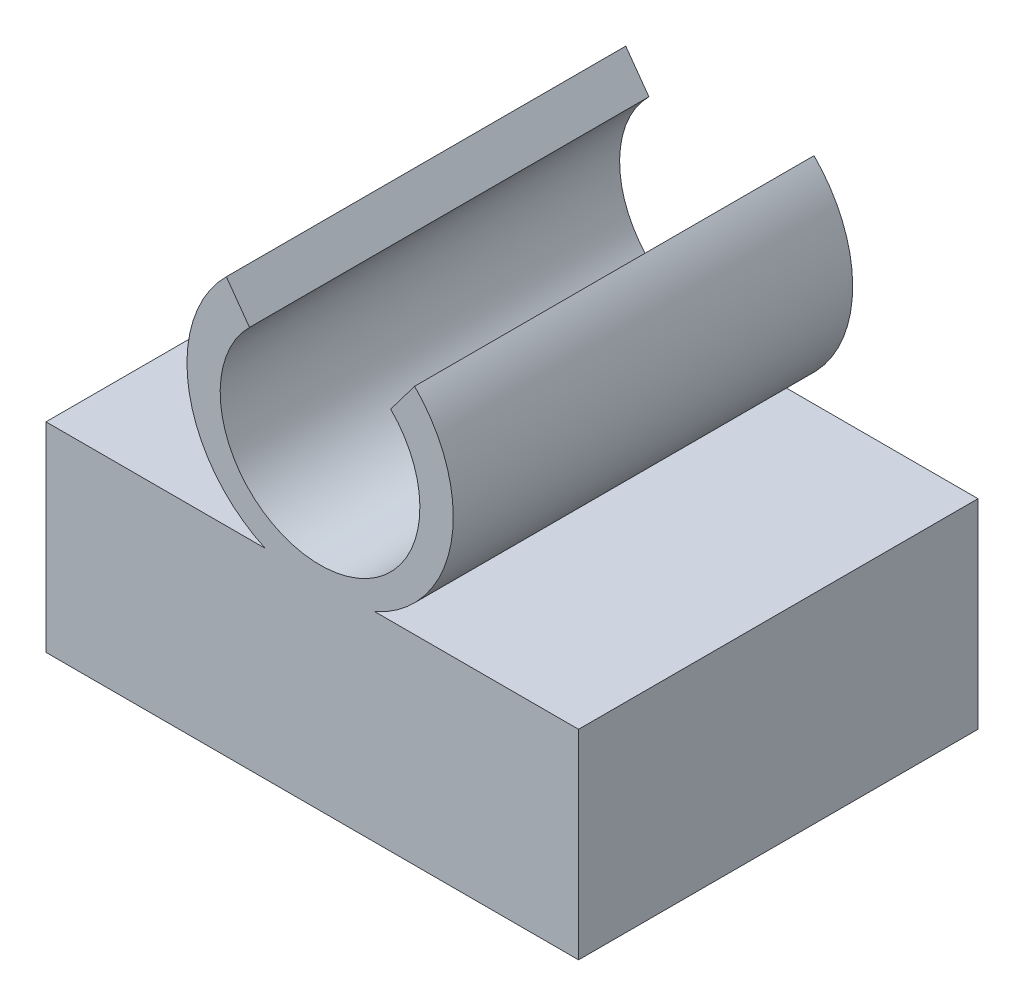
SolidWorks part; units mm, degrees
ref_plane "Front Plane" through (0, 0, 0) normal (0, 0, 1) x (1, 0, 0)
ref_plane "Top Plane" through (0, 0, 0) normal (0, 1, 0) x (1, 0, 0)
ref_plane "Right Plane" through (0, 0, 0) normal (1, 0, 0) x (0, 0, -1)
sketch "Sketch1" plane through (0, 0, 0) normal (0, 1, 0) x (1, 0, 0)
  line L1 (-33.5398, 47.0575) -> (46.4602, 47.0575)
  line L2 (-33.5398, 47.0575) -> (-33.5398, -12.9425)
  line L3 (-33.5398, -12.9425) -> (46.4602, -12.9425)
  line L4 (46.4602, 47.0575) -> (46.4602, -12.9425)
  dimension "D1" = 60
  dimension "D2" = 80
extrude "Boss-Extrude2" add sketch "Sketch1" along normal blind 30
sketch "Sketch2" plane through (0, 0, -47.0575) normal (0, 0, -1) x (-1, 0, 0)
  line L1 (29.7927, 2.2274) -> (-42.2073, 2.2274)
  line L2 (29.7927, 2.2274) -> (29.7927, 27.2274)
  line L3 (29.7927, 27.2274) -> (-42.2073, 27.2274)
  line L4 (-42.2073, 2.2274) -> (-42.2073, 27.2274)
  dimension "D1" = 72
  dimension "D2" = 25
extrude "Cut-Extrude1" cut sketch "Sketch2" against normal blind 55
sketch "Sketch3" plane through (0, 0, -47.0575) normal (0, 0, -1) x (-1, 0, 0)
  line L0 (-18.2417, 57.546) -> (-21.8326, 62.3126)
  line L1 (2.9715, 57.5697) -> (6.4515, 62.4213)
  arc A0 (6.4515, 62.4213) -> (-21.8326, 62.3126) centre (-7.6362, 48.2249) cw
  arc A1 (2.9715, 57.5697) -> (-18.2417, 57.546) centre (-7.6232, 46.9513) cw
extrude "Boss-Extrude3" add sketch "Sketch3" against normal blind 60 separate body
combine bodies "Combine1" operation type add bodies to combine 104 103
